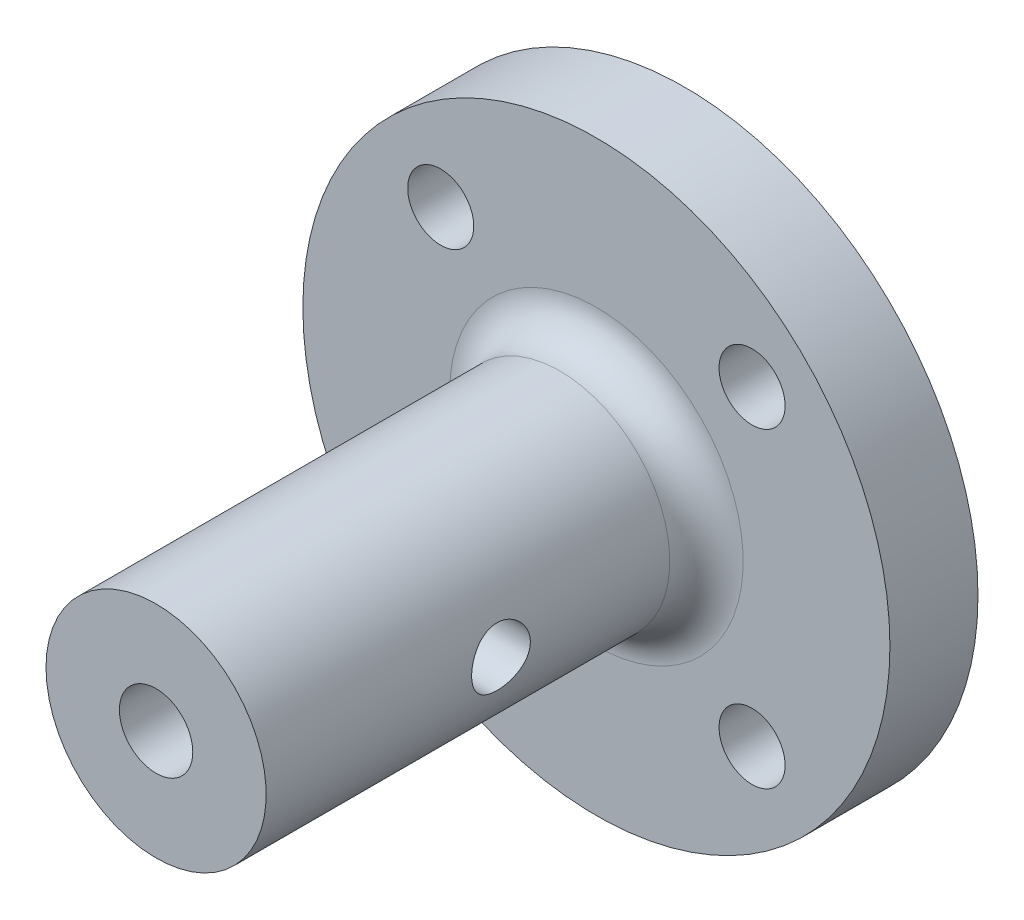
SolidWorks part; units mm, degrees
ref_plane "前视基准面" through (0, 0, 0) normal (0, 0, 1) x (1, 0, 0)
ref_plane "上视基准面" through (0, 0, 0) normal (0, 1, 0) x (1, 0, 0)
ref_plane "右视基准面" through (0, 0, 0) normal (1, 0, 0) x (0, 0, -1)
sketch "草图1" plane through (0, 0, 0) normal (0, 1, 0) x (1, 0, 0)
  line L0 (0, 0) -> (0, -72) construction
  line L1 (0, 0) -> (40, 0)
  line L2 (40, 0) -> (40, -12)
  line L3 (40, -12) -> (15, -12)
  line L4 (15, -12) -> (15, -72)
  line L5 (15, -72) -> (0, -72)
  line L6 (0, -72) -> (0, 0)
revolve "旋转1" add sketch "草图1" angle 360 about L0
ref_plane "基准面1" through (0, 0, 72) normal (0, 0, 1) x (1, 0, 0)
sketch "草图2" plane through (0, 0, 72) normal (0, 0, 1) x (1, 0, 0)
  circle A0 centre (0, 0) radius 5
extrude "切除-拉伸1" cut sketch "草图2" against normal blind 20
sketch "草图3" plane through (0, 0, 0) normal (1, 0, 0) x (0, 0, -1)
  circle A0 centre (-40, 0) radius 4
extrude "切除-拉伸2" cut sketch "草图3" against normal mid plane 162
ref_plane "基准面2" through (0, 0, 12) normal (0, 0, 1) x (1, 0, 0)
sketch "草图4" plane through (0, 0, 12) normal (0, 0, 1) x (1, 0, 0)
  circle A0 centre (21.2132, 21.2132) radius 4.5
  circle A1 centre (-21.2132, 21.2132) radius 4.5
  circle A2 centre (-21.2132, -21.2132) radius 4.5
  circle A3 centre (21.2132, -21.2132) radius 4.5
extrude "切除-拉伸3" cut sketch "草图4" against normal through all
fillet "圆角1" radius 5 1 edges at (-15, 0, 12)
